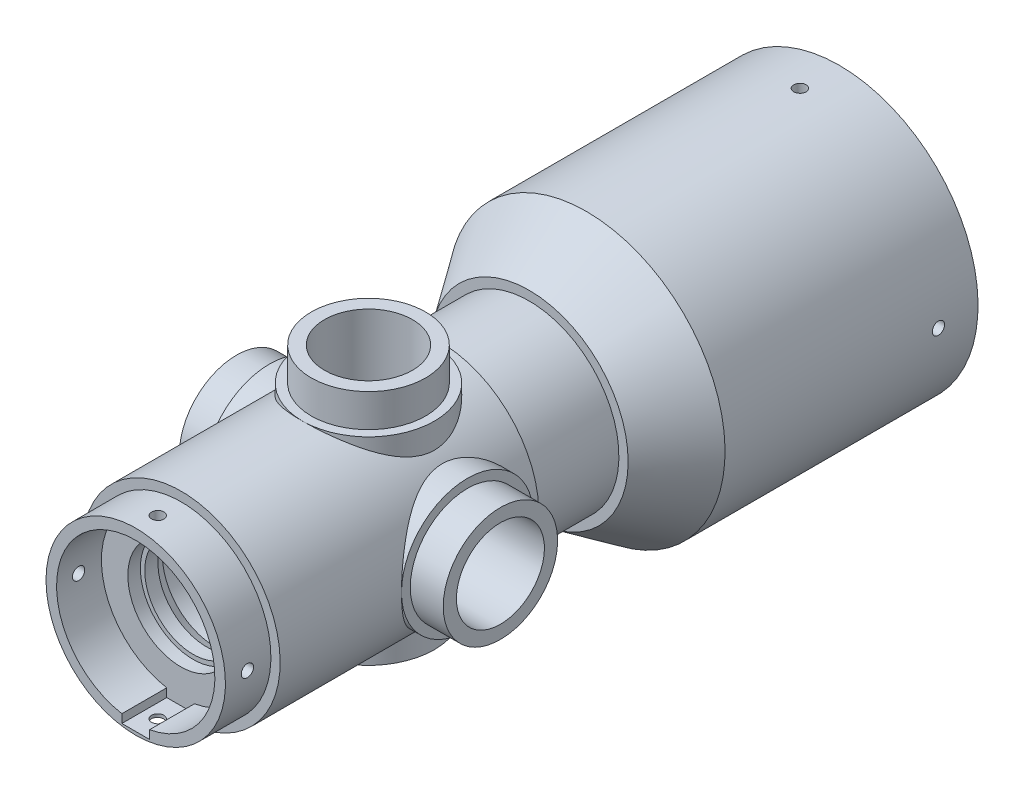
SolidWorks part; units mm, degrees
ref_plane "정면" through (0, 0, 0) normal (0, 0, 1) x (1, 0, 0)
ref_plane "윗면" through (0, 0, 0) normal (0, 1, 0) x (1, 0, 0)
ref_plane "우측면" through (0, 0, 0) normal (1, 0, 0) x (0, 0, -1)
sketch "스케치1" plane through (0, 0, 0) normal (1, 0, 0) x (0, 0, -1)
  line L0 (60, 26.5) -> (76.6842, 26.5)
  line L1 (76.6842, 26.5) -> (80.0406, 22.5)
  line L2 (80.0406, 22.5) -> (179.457, 22.5)
  line L3 (179.457, 22.5) -> (192.4784, 31.5105)
  line L4 (192.4784, 31.5105) -> (250, 31.5105)
  line L5 (250, 31.5105) -> (250, 0) construction
  line L6 (250, 0) -> (0, 0) construction
  line L7 (0, 0) -> (0, 26.5) construction
  line L8 (250, 31.5105) -> (250, 29.5105)
  line L9 (246.9699, 25.5) -> (237.6699, 25.5)
  line L10 (3.1955, 19) -> (65.6714, 19)
  line L11 (246.9699, 25.5) -> (248.5, 29.5105)
  line L12 (248.5, 29.5105) -> (250, 29.5105)
  line L13 (3.1955, 19) -> (2.0194, 20.2311)
  line L14 (2.0194, 20.2311) -> (0, 20.2311)
  line L15 (237.1699, 23.5) -> (233.1699, 23.5)
  line L16 (233.1699, 23.5) -> (233.1699, 27.5105) construction
  line L17 (233.1699, 27.5105) -> (113.1699, 27.5105) construction
  line L18 (228.3783, 27.5105) -> (192.4784, 27.5105)
  line L19 (192.4784, 27.5105) -> (179.457, 12)
  line L20 (179.457, 12) -> (108.0512, 12)
  line L21 (103.0512, 12) -> (103.0512, 11)
  line L22 (103.0512, 11) -> (106.0512, 11)
  line L23 (0, 20.2311) -> (0, 22.5)
  line L24 (78.8512, 12) -> (78.8512, 11)
  line L25 (75.8512, 11) -> (78.8512, 11)
  line L26 (75.8512, 11) -> (65.6714, 19)
  line L27 (179.457, 22.5) -> (179.457, 12) construction
  line L28 (192.4784, 31.5105) -> (192.4784, 27.5105) construction
  line L29 (233.1699, 23.5) -> (228.3783, 27.5105)
  line L30 (228.3783, 27.5105) -> (233.1699, 27.5105) construction
  line L31 (60, 26.5) -> (60, 22.5)
  line L32 (60, 22.5) -> (0, 22.5)
  line L33 (0, 26.5) -> (60, 26.5) construction
  line L34 (106.0512, 11) -> (108.0512, 12)
  line L35 (103.0512, 12) -> (78.8512, 12)
  arc A0 (237.1699, 23.5) -> (237.6699, 25.5) centre (248.2844, 21.7839) cw
  point P2 (237.6699, 25.5)
  point P23 (238.9699, 25.5)
  point P33 (143.9699, 27.5105)
  dimension "D2" = 51
  dimension "D3" = 4
  dimension "D4" = 38
  dimension "D5" = 53
  dimension "D6" = 3
  dimension "D7" = 2
  dimension "D8" = 0.5
  dimension "D9" = 3
  dimension "D10" = 24
  dimension "D11" = 4
  dimension "D12" = 250
  dimension "D13" = 2
  dimension "D14" = 1.5
  dimension "D15" = 8
  dimension "D16" = 22
  dimension "D17" = 1.3
  dimension "D18" = 95
  dimension "D19" = 120
  dimension "D20" = 45
  dimension "D21" = 60
  dimension "D22" = 130
  dimension "D23" = 30.2
  dimension "D24" = 2
  dimension "D25" = 45
revolve "회전1" add sketch "스케치1" angle 360 about L6
sketch "스케치2" plane through (0, 0, 0) normal (0, 1, 0) x (1, 0, 0)
  line L0 (0, 142.9182) -> (0, 0) construction
  circle A0 centre (0, 142.9182) radius 10
  dimension "D1" = 20
extrude "컷-돌출1" cut sketch "스케치2" along normal blind 30
ref_plane "평면1" through (0, 22.5, 0) normal (0, 1, 0) x (1, 0, 0)
sketch "스케치3" plane through (0, 22.5, 0) normal (0, 1, 0) x (1, 0, 0)
  circle A0 centre (0, 142.9182) radius 10
  circle A1 centre (0, 142.9182) radius 13
  dimension "D1" = 20
  dimension "D2" = 26
extrude "보스-돌출1" add sketch "스케치3" along normal mid plane 15
sketch "스케치4" plane through (0, 0, 0) normal (1, 0, 0) x (0, 0, -1)
  line L0 (179.457, 22.5) -> (179.457, 20.4)
  line L1 (24.75, 22.5) -> (-24.75, 22.5) construction
  line L2 (179.457, 22.5) -> (179.457, -22.5) construction
  line L3 (179.457, 20.4) -> (159.157, 20.4)
  line L4 (159.157, 20.4) -> (159.157, 22.5)
  line L5 (159.157, 22.5) -> (179.457, 22.5)
  line L6 (80.5973, 22.5) -> (80.0406, 20.4)
  line L7 (80.0406, 22.5) -> (80.0406, -22.5) construction
  line L8 (80.0406, 20.4) -> (100.3406, 20.4)
  line L9 (100.3406, 20.4) -> (100.3406, 22.5)
  line L10 (100.3406, 22.5) -> (80.5973, 22.5)
  dimension "D1" = 20.3
  dimension "D2" = 20.3
  dimension "D3" = 2.1
  dimension "D4" = 2.1
revolve "컷-회전1" cut sketch "스케치4" angle 360 about axis through (0, 0, -250) along (0, 0, -1)
sketch "스케치5" plane through (0, 22.5, 0) normal (0, 1, 0) x (1, 0, 0)
  circle A0 centre (0, 142.9182) radius 13
  circle A1 centre (0, 142.9182) radius 15
  dimension "D1" = 26
  dimension "D2" = 30
extrude "보스-돌출2" add sketch "스케치5" against normal blind 6
sketch "스케치6" plane through (0, 0, 0) normal (0, 1, 0) x (1, 0, 0)
  line L0 (0, 53.6666) -> (0, 35.3005) construction
  line L1 (0, 3.1955) -> (0, 65.6714) construction
  line L2 (2.7, 53.6666) -> (2.7, 35.3005)
  line L3 (-2.7, 53.6666) -> (-2.7, 35.3005)
  arc A0 (2.7, 53.6666) -> (-2.7, 53.6666) centre (0, 53.6666) ccw
  arc A1 (-2.7, 35.3005) -> (2.7, 35.3005) centre (0, 35.3005) ccw
  point P5 (0, 44.4835)
  dimension "D1" = 2.7
extrude "컷-돌출2" cut sketch "스케치6" against normal blind 30
sketch "스케치7" plane through (0, 0, 0) normal (0, 0, 1) x (1, 0, 0)
  line L0 (24.75, 22.5) -> (-24.75, 22.5) construction
  line L1 (-1.4, 23.6) -> (1.4, 23.6)
  line L2 (-1.4, 23.6) -> (-1.4, 21.4)
  line L3 (-1.4, 21.4) -> (1.4, 21.4)
  line L4 (1.4, 23.6) -> (1.4, 21.4)
  line L5 (-1.4, 23.6) -> (1.4, 21.4) construction
  line L6 (-1.4, 21.4) -> (1.4, 23.6) construction
  line L7 (0, 30) -> (0, 12) construction
  line L8 (0, 22.5) -> (0, 0) construction
  point P0 (0, 22.5)
  dimension "D1" = 2.8
  dimension "D2" = 2.2
extrude "보스-돌출3" add sketch "스케치7" against normal blind 27
chamfer "모따기1" distance 1 angle 45 2 edges at (0, 23.6, 0) (0, 23.6, -27)
pattern_circular "원형 패턴1" count 2 over 90 about axis through (0, 0, -65.6714) along (0, 0, 1) of "보스-돌출1", "보스-돌출2", "컷-돌출1"
pattern_circular "원형 패턴2" count 2 over 90 about axis through (0, 0, -250) along (0, 0, -1) of "보스-돌출1", "보스-돌출2", "컷-돌출1"
ref_plane "평면2" through (0, 0, -90) normal (0, 0, 1) x (1, 0, 0)
sketch "스케치8" plane through (0, 0, -90) normal (0, 0, 1) x (1, 0, 0)
  line L1 (-50.3448, -38.0185) -> (50.3448, -38.0185)
  line L2 (-50.3448, -38.0185) -> (-50.3448, 38.0185)
  line L3 (-50.3448, 38.0185) -> (50.3448, 38.0185)
  line L4 (50.3448, -38.0185) -> (50.3448, 38.0185)
  line L5 (-50.3448, -38.0185) -> (50.3448, 38.0185) construction
  line L6 (-50.3448, 38.0185) -> (50.3448, -38.0185) construction
  point P0 (0, 0)
extrude "컷-돌출3" cut sketch "스케치8" along normal through all
sketch "스케치10" plane through (0, 0, -90) normal (0, 0, 1) x (1, 0, 0)
  line L1 (-3.15, -19.65) -> (3.15, -19.65)
  line L2 (-3.15, -19.65) -> (-3.15, -16.35)
  line L3 (-3.15, -16.35) -> (3.15, -16.35)
  line L4 (3.15, -19.65) -> (3.15, -16.35)
  line L5 (-3.15, -19.65) -> (3.15, -16.35) construction
  line L6 (-3.15, -16.35) -> (3.15, -19.65) construction
  circle A0 centre (0, 0) radius 12
  circle A1 centre (0, 0) radius 12 construction
  circle A2 centre (0, 0) radius 18
  point P6 (0, -18)
  dimension "D1" = 36
  dimension "D2" = 3.3
  dimension "D3" = 6.3
sketch "스케치13" plane through (0, 30, 0) normal (0, 1, 0) x (1, 0, 0)
  circle A0 centre (0, 142.9182) radius 11
  dimension "D1" = 22
extrude "컷-돌출4" cut sketch "스케치10" against normal blind 10.2 contours L4 A2 L2 L3 A0 | L2 A2 L4 L3 | A2 L2 L1 L4 | A0
sketch "스케치14" plane through (0, 0, 0) normal (1, 0, 0) x (0, 0, -1)
  line L0 (100.3406, 0) -> (90, 0) construction
  line L1 (90, 34.6615) -> (90, -34.6615) construction
  line L2 (192.4784, 0) -> (250, 0) construction
  line L3 (250, -31.5105) -> (250, 31.5105) construction
  circle A0 centre (95, 0) radius 1.4
  circle A1 centre (241, 0) radius 1.4
  dimension "D1" = 2.8
  dimension "D3" = 2.8
  dimension "D2" = 5
  dimension "D4" = 9
extrude "컷-돌출5" cut sketch "스케치14" against normal through all both and the other way through all
pattern_circular "원형 패턴3" count 2 over 90 of "컷-돌출5"
pattern_circular "원형 패턴4" count 2 over 180 about axis through (0, 0, -250) along (0, 0, -1) of "보스-돌출2", "컷-돌출1"
sketch "스케치15" plane through (0, -22.5, 0) normal (0, -1, 0) x (1, 0, 0)
  circle A0 centre (0, -142.9182) radius 13
  circle A1 centre (0, -142.9182) radius 10
  dimension "D1" = 26
  dimension "D2" = 20
extrude "보스-돌출4" add sketch "스케치15" against normal blind 5
